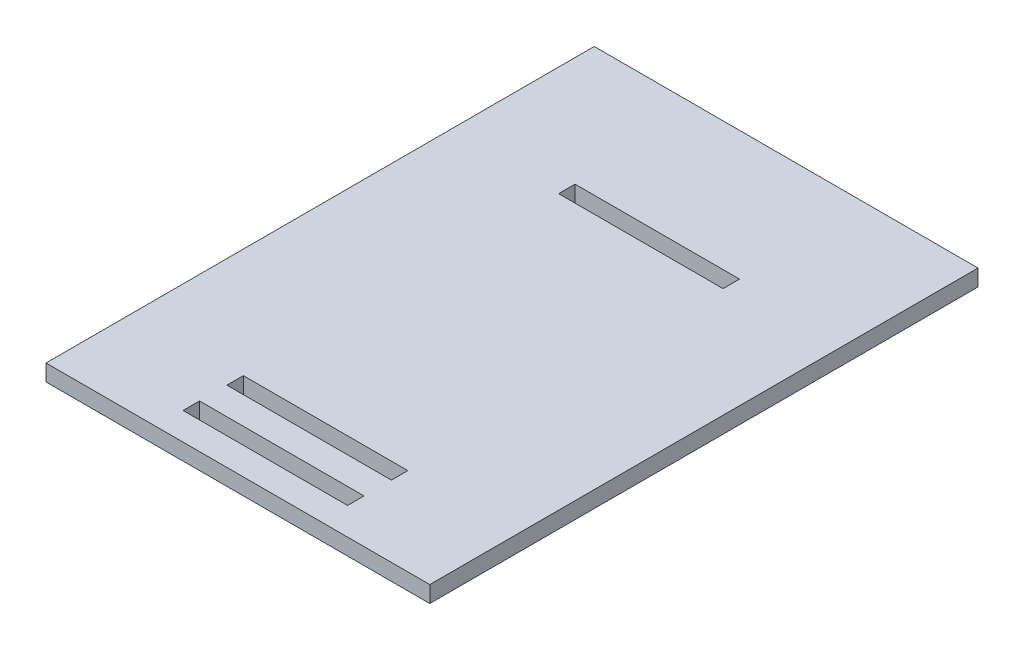
SolidWorks part; units mm, degrees
ref_plane "Front Plane" through (0, 0, 0) normal (0, 0, 1) x (1, 0, 0)
ref_plane "Top Plane" through (0, 0, 0) normal (0, 1, 0) x (1, 0, 0)
ref_plane "Right Plane" through (0, 0, 0) normal (1, 0, 0) x (0, 0, -1)
sketch "Sketch1" plane through (0, 0, 0) normal (0, 1, 0) x (1, 0, 0)
  line L1 (35, 50) -> (-35, 50)
  line L2 (35, 50) -> (35, -50)
  line L3 (35, -50) -> (-35, -50)
  line L4 (-35, 50) -> (-35, -50)
  line L5 (35, 50) -> (-35, -50) construction
  line L6 (35, -50) -> (-35, 50) construction
  point P0 (0, 0)
  dimension "D1" = 70
  dimension "D2" = 100
extrude "Boss-Extrude1" add sketch "Sketch1" along normal blind 3
sketch "Sketch2" plane through (0, 3, 0) normal (0, 1, 0) x (1, 0, 0)
  line L0 (-35, -50) -> (35, -50) construction
  line L1 (15, -42) -> (-15, -42)
  line L2 (15, -42) -> (15, -45)
  line L3 (15, -45) -> (-15, -45)
  line L4 (-15, -42) -> (-15, -45)
  line L5 (15, -42) -> (-15, -45) construction
  line L6 (15, -45) -> (-15, -42) construction
  line L11 (15, -34) -> (-15, -34)
  line L12 (15, -34) -> (15, -37)
  line L13 (15, -37) -> (-15, -37)
  line L14 (15, 23.5) -> (-15, 23.5)
  line L15 (15, 23.5) -> (15, 26.5)
  line L16 (15, 26.5) -> (-15, 26.5)
  line L17 (-15, 23.5) -> (-15, 26.5)
  line L18 (15, 23.5) -> (-15, 26.5) construction
  line L19 (15, 26.5) -> (-15, 23.5) construction
  line L20 (-15, -34) -> (-15, -37)
  line L21 (15, -34) -> (-15, -37) construction
  line L22 (15, -37) -> (-15, -34) construction
  point P0 (0, -43.5)
  point P6 (0, -35.5)
  point P8 (0, -50)
  point P9 (0, 25)
  point P18 (0, 0)
  point P19 (0, 0)
  dimension "D1" = 30
  dimension "D2" = 3
  dimension "D3" = 5
  dimension "D5" = 5
  dimension "D6" = 75
  dimension "D4" = 3
extrude "Cut-Extrude1" cut sketch "Sketch2" against normal through all
